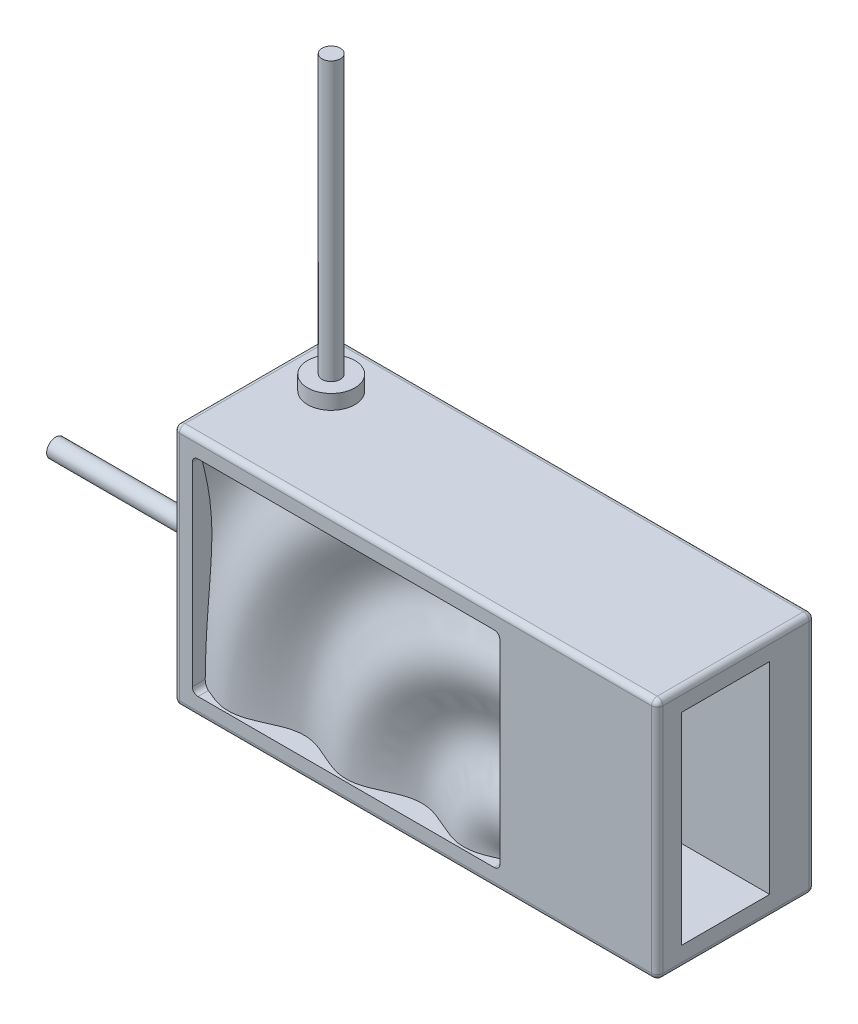
SolidWorks part; units mm, degrees
ref_plane "Front Plane" through (0, 0, 0) normal (0, 0, 1) x (1, 0, 0)
ref_plane "Top Plane" through (0, 0, 0) normal (0, 1, 0) x (1, 0, 0)
ref_plane "Right Plane" through (0, 0, 0) normal (1, 0, 0) x (0, 0, -1)
sketch "Sketch1" plane through (0, 0, 0) normal (0, 0, 1) x (1, 0, 0)
  line L1 (-21.5, -10.8) -> (21.5, -10.8)
  line L2 (-21.5, -10.8) -> (-21.5, 10.8)
  line L3 (-21.5, 10.8) -> (21.5, 10.8)
  line L4 (21.5, -10.8) -> (21.5, 10.8)
  line L5 (-21.5, -10.8) -> (21.5, 10.8) construction
  line L6 (-21.5, 10.8) -> (21.5, -10.8) construction
  point P0 (0, 0)
  dimension "D1" = 43
  dimension "D2" = 21.6
extrude "Boss-Extrude1" add sketch "Sketch1" along normal blind 14
sketch "Sketch2" plane through (0, 0, 14) normal (0, 0, 1) x (1, 0, 0)
  line L0 (21.5, 10.8) -> (-21.5, 10.8) construction
  line L1 (-19.85, 9.15) -> (7.5, 9.15)
  line L2 (-19.85, 9.15) -> (-19.85, -9.15)
  line L3 (-19.85, -9.15) -> (7.5, -9.15)
  line L4 (7.5, 9.15) -> (7.5, -9.15)
  line L5 (-21.5, 10.8) -> (-21.5, -10.8) construction
  line L6 (-21.5, -10.8) -> (21.5, -10.8) construction
  line L7 (21.5, -10.8) -> (21.5, 10.8) construction
  dimension "D1" = 1.65
  dimension "D2" = 1.65
  dimension "D3" = 1.65
  dimension "D4" = 14
extrude "Cut-Extrude1" cut sketch "Sketch2" against normal blind 2
sketch "Sketch3" plane through (21.5, 0, 0) normal (1, 0, 0) x (0, 0, -1)
  line L0 (-14, 10.8) -> (0, 10.8) construction
  line L1 (-11.85, 8.97) -> (-4, 8.97)
  line L2 (-11.85, 8.97) -> (-11.85, -8.97)
  line L3 (-11.85, -8.97) -> (-4, -8.97)
  line L4 (-4, 8.97) -> (-4, -8.97)
  line L5 (-14, -10.8) -> (0, -10.8) construction
  line L6 (-14, -10.8) -> (-14, 10.8) construction
  line L7 (0, -10.8) -> (0, 10.8) construction
  dimension "D1" = 1.83
  dimension "D2" = 1.83
  dimension "D3" = 2.15
  dimension "D4" = 4
extrude "Cut-Extrude2" cut sketch "Sketch3" against normal blind 8
sketch "Sketch4" plane through (0, -9.15, 0) normal (0, 1, 0) x (1, 0, 0)
  line L0 (-32.5835, -10.147) -> (-32.5835, -12.2656)
  line L5 (-32.5835, -10.147) -> (7.4165, -10.147)
  line L6 (7.4165, -10.147) -> (7.4165, -12.6974)
  spline S0 degree 4 poles (-36.5435, -13.5563) (-36.4184, -13.5172) (-36.1704, -13.4319) (-35.8052, -13.2859) (-35.3263, -13.0727) (-34.8492, -12.8555) (-34.4274, -12.675) (-34.0592, -12.5368) (-33.7465, -12.4382) (-33.4932, -12.3713) (-33.268, -12.3254) (-33.0733, -12.2962) (-32.9297, -12.2807) (-32.8272, -12.2733) (-32.7207, -12.2681) (-32.6251, -12.2654) (-32.554, -12.2651) (-32.4432, -12.2681) (-32.3332, -12.2735) (-32.2045, -12.2836) (-32.0583, -12.301) (-31.8834, -12.3287) (-31.6867, -12.3697) (-31.4918, -12.4191) (-31.299, -12.476) (-31.0744, -12.5506) (-30.8193, -12.6457) (-30.5346, -12.7625) (-30.2201, -12.9005) (-29.8291, -13.0773) (-29.3588, -13.2878) (-28.7858, -13.5195) (-28.0906, -13.719) (-27.2938, -13.8056) (-26.4191, -13.6934) (-25.4914, -13.37) (-24.5022, -12.9086) (-23.3922, -12.4153) (-22.1243, -12.1545) (-20.858, -12.4065) (-19.7519, -12.8938) (-18.7692, -13.3532) (-17.8466, -13.6822) (-16.9736, -13.8046) (-16.0093, -13.7118) (-15.0055, -13.3743) (-14.0475, -12.9091) (-13.0494, -12.4827) (-12.1334, -12.2625) (-11.3353, -12.243) (-10.4098, -12.421) (-9.4009, -12.826) (-8.4349, -13.303) (-7.4171, -13.6752) (-6.4571, -13.8039) (-5.6065, -13.7213) (-4.6828, -13.4278) (-3.699, -12.9759) (-2.7565, -12.5438) (-1.7953, -12.2732) (-0.9661, -12.2431) (-0.3159, -12.3437) (0.2657, -12.516) (0.7836, -12.7176) (1.4057, -12.9934) (2.1361, -13.3293) (2.8474, -13.6048) (3.552, -13.7503) (4.0996, -13.7732) (4.4757, -13.7514) (4.9171, -13.6804) (5.4047, -13.5493) (5.8799, -13.3708) (6.3049, -13.187) (6.6975, -13.0113) (6.938, -12.9006) (7.312, -12.74) (7.4713, -12.6739) (7.7831, -12.5542) (7.9985, -12.4825) (8.249, -12.4079) (8.4884, -12.351) (8.7379, -12.305) (8.986, -12.2759) (9.2415, -12.2623) (9.5002, -12.2669) (9.8289, -12.2957) (10.2232, -12.3668) (10.6089, -12.4764) (10.9852, -12.6126) (11.2324, -12.7131) (11.3553, -12.765) (11.4165, -12.7914) knots 0 0 0 0 0 0.010417 0.020835 0.031252 0.04167 0.052087 0.057296 0.062505 0.067713 0.072922 0.075526 0.078131 0.079433 0.080735 0.083339 0.085337 0.087334 0.089331 0.091328 0.095323 0.099317 0.103312 0.107307 0.111301 0.115296 0.122119 0.128943 0.135766 0.14259 0.156237 0.169884 0.184885 0.199885 0.219547 0.23921 0.26282 0.28643 0.31643 0.339777 0.363125 0.3828 0.402474 0.417474 0.432475 0.459256 0.486038 0.502278 0.518519 0.533734 0.548949 0.576756 0.604563 0.619563 0.634563 0.653213 0.671862 0.696235 0.720608 0.735608 0.750608 0.76165 0.772692 0.783733 0.794775 0.815714 0.836652 0.844152 0.851652 0.859153 0.866653 0.879411 0.89217 0.89855 0.904929 0.911308 0.917688 0.922675 0.927663 0.932651 0.937638 0.942626 0.947614 0.952601 0.957589 0.96289 0.968192 0.978795 0.989397 0.994699 1 1 1 1 1 construction
  spline S1 degree 4 poles (-32.5835, -12.2656) (-32.5625, -12.2656) (-32.5204, -12.266) (-32.4432, -12.2681) (-32.3332, -12.2735) (-32.2045, -12.2836) (-32.0583, -12.301) (-31.8834, -12.3287) (-31.6867, -12.3697) (-31.4918, -12.4191) (-31.299, -12.476) (-31.0744, -12.5506) (-30.8193, -12.6457) (-30.5346, -12.7625) (-30.2201, -12.9005) (-29.8291, -13.0773) (-29.3588, -13.2878) (-28.7858, -13.5195) (-28.0906, -13.719) (-27.2938, -13.8056) (-26.4191, -13.6934) (-25.4914, -13.37) (-24.5022, -12.9086) (-23.3922, -12.4153) (-22.1243, -12.1545) (-20.858, -12.4065) (-19.7519, -12.8938) (-18.7692, -13.3532) (-17.8466, -13.6822) (-16.9736, -13.8046) (-16.0093, -13.7118) (-15.0055, -13.3743) (-14.0475, -12.9091) (-13.0494, -12.4827) (-12.1334, -12.2625) (-11.3353, -12.243) (-10.4098, -12.421) (-9.4009, -12.826) (-8.4349, -13.303) (-7.4171, -13.6752) (-6.4571, -13.8039) (-5.6065, -13.7213) (-4.6828, -13.4278) (-3.699, -12.9759) (-2.7565, -12.5438) (-1.7953, -12.2732) (-0.9661, -12.2431) (-0.3159, -12.3437) (0.2657, -12.516) (0.7836, -12.7176) (1.4057, -12.9934) (2.1361, -13.3293) (2.8474, -13.6048) (3.552, -13.7503) (4.0996, -13.7732) (4.4757, -13.7514) (4.9171, -13.6804) (5.4047, -13.5493) (5.8799, -13.3708) (6.3049, -13.187) (6.6975, -13.0113) (6.938, -12.9006) (7.2347, -12.7732) (7.3545, -12.7227) (7.4165, -12.6974) knots 0.083339 0.083339 0.083339 0.083339 0.083339 0.085337 0.087334 0.089331 0.091328 0.095323 0.099317 0.103312 0.107307 0.111301 0.115296 0.122119 0.128943 0.135766 0.14259 0.156237 0.169884 0.184885 0.199885 0.219547 0.23921 0.26282 0.28643 0.31643 0.339777 0.363125 0.3828 0.402474 0.417474 0.432475 0.459256 0.486038 0.502278 0.518519 0.533734 0.548949 0.576756 0.604563 0.619563 0.634563 0.653213 0.671862 0.696235 0.720608 0.735608 0.750608 0.76165 0.772692 0.783733 0.794775 0.815714 0.836652 0.844152 0.851652 0.859153 0.866653 0.879411 0.89217 0.89855 0.904929 0.911308 0.917688 0.917688 0.917688 0.917688 0.917688
revolve "Revolve2" add sketch "Sketch4" angle 90 about axis through (7.5, -9.15, 12) along (0, 0, 1)
sketch "Sketch5" plane through (0, 0, 0) normal (0, 0, 1) x (1, 0, 0)
  line L1 (-21.5, -10.8) -> (21.5, -10.8)
  line L2 (-21.5, -10.8) -> (-21.5, 10.8)
  line L3 (-21.5, 10.8) -> (21.5, 10.8)
  line L4 (21.5, -10.8) -> (21.5, 10.8)
  line L5 (-21.5, -10.8) -> (21.5, 10.8) construction
  line L6 (-21.5, 10.8) -> (21.5, -10.8) construction
  line L11 (-42.9029, 42.5501) -> (49.3329, 42.5501)
  line L12 (-42.9029, 42.5501) -> (-42.9029, -30.8838)
  line L13 (-42.9029, -30.8838) -> (49.3329, -30.8838)
  line L14 (49.3329, 42.5501) -> (49.3329, -30.8838)
  point P0 (0, 0)
  dimension "D1" = 43
  dimension "D2" = 21.6
extrude "Cut-Extrude3" cut sketch "Sketch5" along normal blind 23
sketch "Sketch6" plane through (-21.5, 0, 0) normal (-1, 0, 0) x (0, 0, 1)
  line L0 (14, -10.8) -> (0, -10.8) construction
  line L1 (0, 10.8) -> (0, -10.8) construction
  circle A0 centre (4.5, -5.8) radius 2.105
  circle A1 centre (4.5, -5.8) radius 0.81
  dimension "D1" = 4.21
  dimension "D2" = 1.62
  dimension "D3" = 5
  dimension "D4" = 4.5
extrude "Boss-Extrude2" add sketch "Sketch6" along normal blind 1.3
sketch "Sketch7" plane through (0, 10.8, -10.8) normal (0, -1, 0) x (1, 0, 0)
  line L2 (21.5, 10.8) -> (-21.5, 10.8) construction
  line L3 (-21.5, 24.8) -> (-21.5, 10.8) construction
  circle A0 centre (-17, 15.3) radius 2.105
  circle A1 centre (-17, 15.3) radius 0.81
  dimension "D1" = 4.21
  dimension "D2" = 1.62
  dimension "D3" = 4.5
  dimension "D4" = 4.5
extrude "Boss-Extrude3" add sketch "Sketch7" against normal blind 1.3
sketch "Sketch8" plane through (-21.5, 0, 0) normal (-1, 0, 0) x (0, 0, 1)
  circle A0 centre (4.5, -5.8) radius 0.81
extrude "Boss-Extrude4" add sketch "Sketch8" along normal blind 20
sketch "Sketch9" plane through (0, 10.8, 0) normal (0, 1, 0) x (1, 0, 0)
  circle A0 centre (-17, -4.5) radius 0.8152
extrude "Boss-Extrude5" add sketch "Sketch9" along normal blind 26
fillet "Fillet1" radius 0.5 16 edges at (-21.5, -10.8, 7) (0, -10.8, 14) (21.5, -10.8, 7) (0, 10.8, 0) (-21.5, 0, 0) (0, -10.8, 0) (21.5, 0, 0) (7.5, -9.15, 13) (7.5, 9.15, 13.1794) (-19.85, 9.15, 13.6561) (-19.85, -9.15, 13.4283) (-21.5, 0, 14) (-21.5, 10.8, 7) (0, 10.8, 14) (21.5, 10.8, 7) (21.5, 0, 14)
